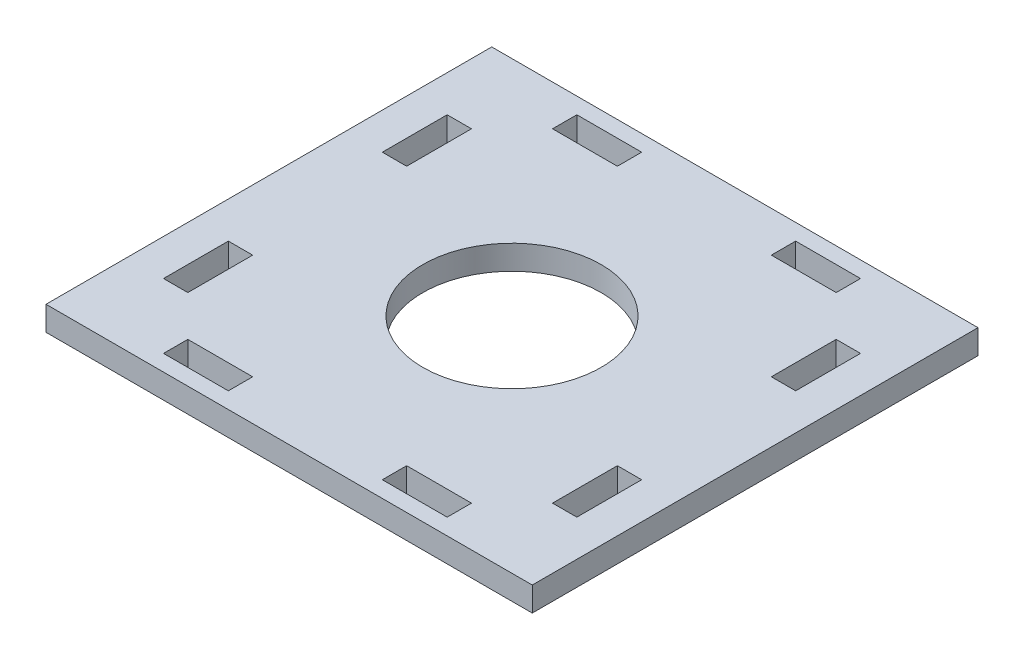
SolidWorks part; units mm, degrees
ref_plane "前视基准面" through (0, 0, 0) normal (0, 0, 1) x (1, 0, 0)
ref_plane "上视基准面" through (0, 0, 0) normal (0, 1, 0) x (1, 0, 0)
ref_plane "右视基准面" through (0, 0, 0) normal (1, 0, 0) x (0, 0, -1)
other "Configuration Table"
sketch "草图1" plane through (0, 0, 0) normal (0, 1, 0) x (1, 0, 0)
  line L0 (-30, -27.5) -> (-10, -72.5)
  line L1 (-30, 27.5) -> (30, 27.5)
  line L2 (-30, 27.5) -> (-30, -27.5)
  line L3 (-30, -27.5) -> (30, -27.5)
  line L4 (30, 27.5) -> (30, -27.5)
  line L5 (-30, 27.5) -> (30, -27.5) construction
  line L6 (-30, -27.5) -> (30, 27.5) construction
  line L7 (-10, -27.5) -> (10, -27.5)
  line L8 (-10, -27.5) -> (-10, -72.5)
  line L9 (-10, -72.5) -> (10, -72.5)
  line L10 (10, -27.5) -> (10, -72.5)
  line L11 (10, -72.5) -> (30, -27.5)
  line L12 (0, -27.5) -> (0, -37.5) construction
  line L13 (0, -37.5) -> (0, -57.5) construction
  line L14 (-4.6142, 0) -> (3.837, 0) construction
  line L15 (-22.5, 22.5) -> (22.5, 22.5) construction
  line L16 (-22.5, 22.5) -> (-22.5, -22.5) construction
  line L17 (-22.5, -22.5) -> (22.5, -22.5) construction
  line L18 (22.5, 22.5) -> (22.5, -22.5) construction
  line L19 (-22.5, 22.5) -> (22.5, -22.5) construction
  line L20 (-22.5, -22.5) -> (22.5, 22.5) construction
  line L21 (-22.5, 17.5) -> (-25.5, 17.5)
  line L22 (-22.5, 17.5) -> (-22.5, 9.5)
  line L23 (-22.5, 9.5) -> (-25.5, 9.5)
  line L24 (-25.5, 17.5) -> (-25.5, 9.5)
  line L25 (-22.5, -9.5) -> (-25.5, -9.5)
  line L26 (-25.5, -17.5) -> (-25.5, -9.5)
  line L27 (-22.5, -17.5) -> (-25.5, -17.5)
  line L28 (-22.5, -17.5) -> (-22.5, -9.5)
  line L53 (17.5, 22.5) -> (9.5, 22.5)
  line L54 (17.5, 22.5) -> (17.5, 25.5)
  line L55 (17.5, 25.5) -> (9.5, 25.5)
  line L56 (9.5, 22.5) -> (9.5, 25.5)
  line L57 (-9.5, 22.5) -> (-9.5, 25.5)
  line L58 (-17.5, 25.5) -> (-9.5, 25.5)
  line L59 (-17.5, 22.5) -> (-17.5, 25.5)
  line L60 (-17.5, 22.5) -> (-9.5, 22.5)
  line L61 (-17.5, -22.5) -> (-9.5, -22.5)
  line L62 (-17.5, -22.5) -> (-17.5, -25.5)
  line L63 (-17.5, -25.5) -> (-9.5, -25.5)
  line L64 (-9.5, -22.5) -> (-9.5, -25.5)
  line L65 (9.5, -22.5) -> (9.5, -25.5)
  line L66 (17.5, -25.5) -> (9.5, -25.5)
  line L67 (17.5, -22.5) -> (17.5, -25.5)
  line L68 (17.5, -22.5) -> (9.5, -22.5)
  line L69 (22.5, 17.5) -> (25.5, 17.5)
  line L70 (25.5, 17.5) -> (25.5, 9.5)
  line L71 (22.5, 9.5) -> (25.5, 9.5)
  line L72 (22.5, 17.5) -> (22.5, 9.5)
  line L73 (22.5, -17.5) -> (22.5, -9.5)
  line L74 (22.5, -17.5) -> (25.5, -17.5)
  line L75 (25.5, -17.5) -> (25.5, -9.5)
  line L76 (22.5, -9.5) -> (25.5, -9.5)
  circle A0 centre (0, -37.5) radius 2
  circle A1 centre (0, -57.5) radius 2
  point P0 (0, 0)
  point P10 (0, -72.5)
  point P16 (0, 0)
  dimension "D5" = 4
  dimension "D7" = 20
  dimension "D1" = 60
  dimension "D2" = 55
  dimension "D3" = 20
  dimension "D4" = 45
  dimension "D6" = 10
  dimension "D8" = 45
  dimension "D9" = 45
  dimension "D10" = 3
  dimension "D11" = 8
  dimension "D12" = 5
extrude "凸台-拉伸1" add sketch "草图1" along normal blind 3 contours L4 L1 L2 L3 | L8 L3 L0 | L10 L3 L8 L9 A1 A0 | L10 L11 L3
sketch "草图2" plane through (0, 3, 0) normal (0, 1, 0) x (1, 0, 0)
  line L0 (30, 27.5) -> (30, -27.5) construction
  line L1 (-30, -27.5) -> (30, -27.5)
  line L2 (-30, -27.5) -> (-30, -77.5)
  line L3 (-30, -77.5) -> (30, -77.5)
  line L4 (30, -27.5) -> (30, -77.5)
  point P4 (30, -27.5)
  dimension "D1" = 50
extrude "切除-拉伸1" cut sketch "草图2" against normal blind 10
sketch "草图3" plane through (0, 3, 0) normal (0, 1, 0) x (1, 0, 0)
  circle A0 centre (0, 0) radius 11
  dimension "D1" = 22
extrude "切除-拉伸2" cut sketch "草图3" against normal blind 10
